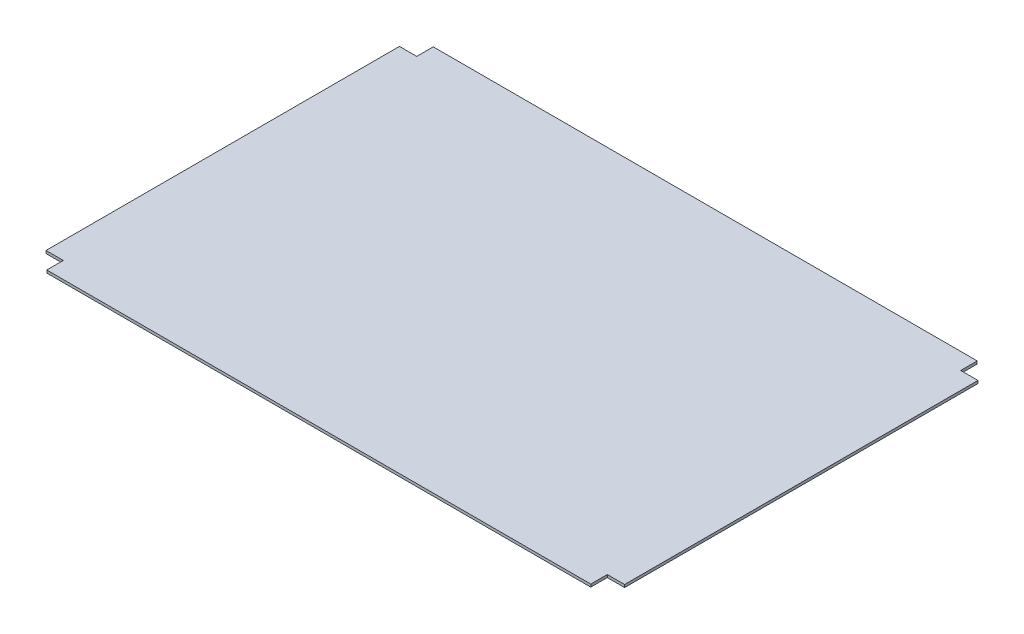
SolidWorks part; units mm, degrees
ref_plane "Alzado" through (0, 0, 0) normal (0, 0, 1) x (1, 0, 0)
ref_plane "Planta" through (0, 0, 0) normal (0, 1, 0) x (1, 0, 0)
ref_plane "Vista lateral" through (0, 0, 0) normal (1, 0, 0) x (0, 0, -1)
sketch "Croquis1" plane through (0, 0, 0) normal (0, 1, 0) x (1, 0, 0)
  line L1 (753, -503) -> (-753, -503)
  line L2 (753, -503) -> (753, 503)
  line L3 (753, 503) -> (-753, 503)
  line L4 (-753, -503) -> (-753, 503)
  line L5 (753, -503) -> (-753, 503) construction
  line L6 (753, 503) -> (-753, -503) construction
  point P0 (0, 0)
  dimension "D1" = 1506
  dimension "D2" = 1006
extrude "Saliente-Extruir1" add sketch "Croquis1" along normal blind 7
sketch "Croquis2" plane through (0, 7, 0) normal (0, 1, 0) x (1, 0, 0)
  line L0 (-753, 503) -> (-708, 503)
  line L1 (753, 503) -> (-753, 503) construction
  line L2 (-708, 503) -> (-708, 460)
  line L3 (-708, 460) -> (-753, 460)
  line L4 (-753, 503) -> (-753, -503) construction
  line L5 (-753, 503) -> (-753, 460)
  line L6 (0, 503) -> (0, -503) construction
  line L7 (-753, -503) -> (753, -503) construction
  line L8 (753, 0) -> (-753, 0) construction
  line L9 (753, -503) -> (753, 503) construction
  line L10 (-708, -460) -> (-753, -460)
  line L11 (-753, -503) -> (-753, -460)
  line L12 (-753, -503) -> (-708, -503)
  line L13 (-708, -503) -> (-708, -460)
  line L14 (753, -503) -> (753, -460)
  line L15 (753, -503) -> (708, -503)
  line L16 (708, -503) -> (708, -460)
  line L17 (708, -460) -> (753, -460)
  line L18 (708, 460) -> (753, 460)
  line L19 (753, 503) -> (753, 460)
  line L20 (753, 503) -> (708, 503)
  line L21 (708, 503) -> (708, 460)
  dimension "D1" = 45
  dimension "D2" = 43
extrude "Cortar-Extruir1" cut sketch "Croquis2" against normal blind 10
